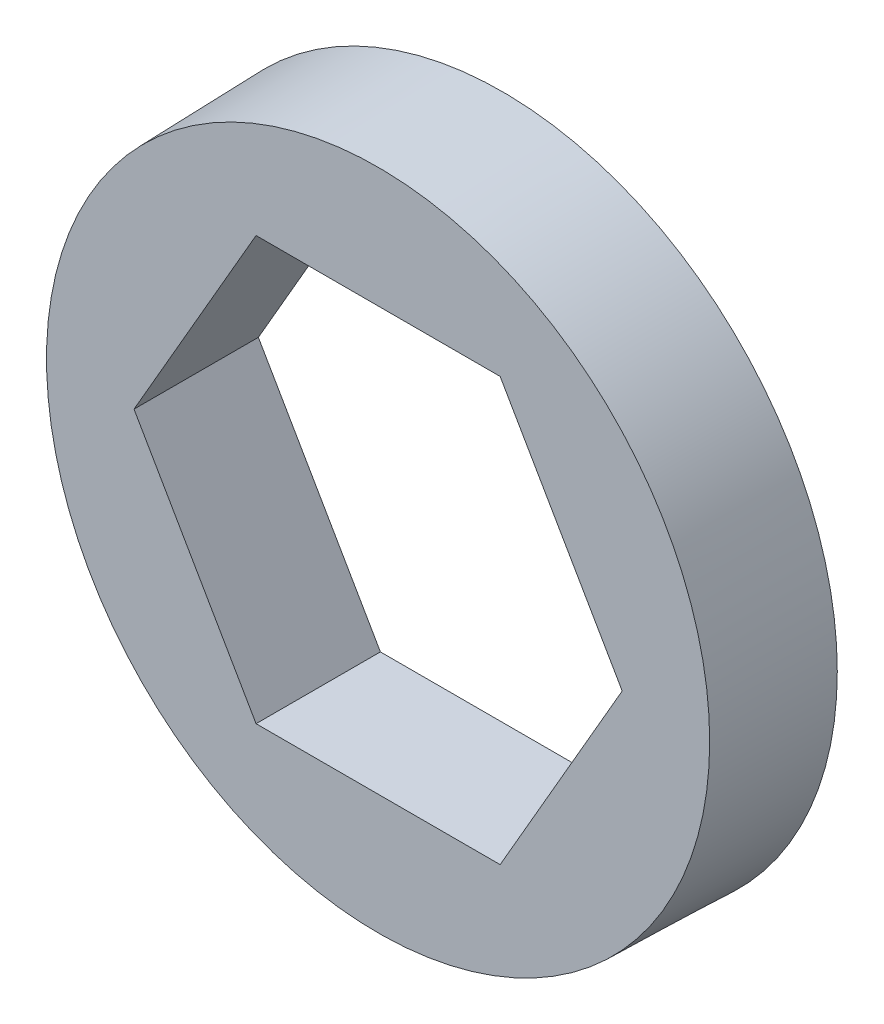
SolidWorks part; units mm, degrees
ref_plane "Front Plane" through (0, 0, 0) normal (0, 0, 1) x (1, 0, 0)
ref_plane "Top Plane" through (0, 0, 0) normal (0, 1, 0) x (1, 0, 0)
ref_plane "Right Plane" through (0, 0, 0) normal (1, 0, 0) x (0, 0, -1)
sketch "Sketch1" plane through (0, 0, 0) normal (0, 1, 0) x (1, 0, 0)
  line L0 (4.0393, 0.75) -> (0, 0.75)
  line L1 (0, 0.75) -> (0, -0.75)
  line L2 (0, -0.75) -> (4, -0.75)
  line L3 (4, -0.75) -> (4.0393, 0.75)
  line L4 (0, 0.75) -> (0, -0.75) construction
revolve "Revolve1" add sketch "Sketch1" angle 360 about L4
sketch "Sketch2" plane through (0, 0, -0.75) normal (0, 0, -1) x (-1, 0, 0)
  line L0 (-2.9445, 0) -> (-1.4722, -2.55)
  line L1 (-1.4722, -2.55) -> (1.4722, -2.55)
  line L2 (1.4722, -2.55) -> (2.9445, 0)
  line L3 (2.9445, 0) -> (1.4722, 2.55)
  line L4 (1.4722, 2.55) -> (-1.4722, 2.55)
  line L5 (-1.4722, 2.55) -> (-2.9445, 0)
extrude "Cut-Extrude1" cut sketch "Sketch2" against normal through all
